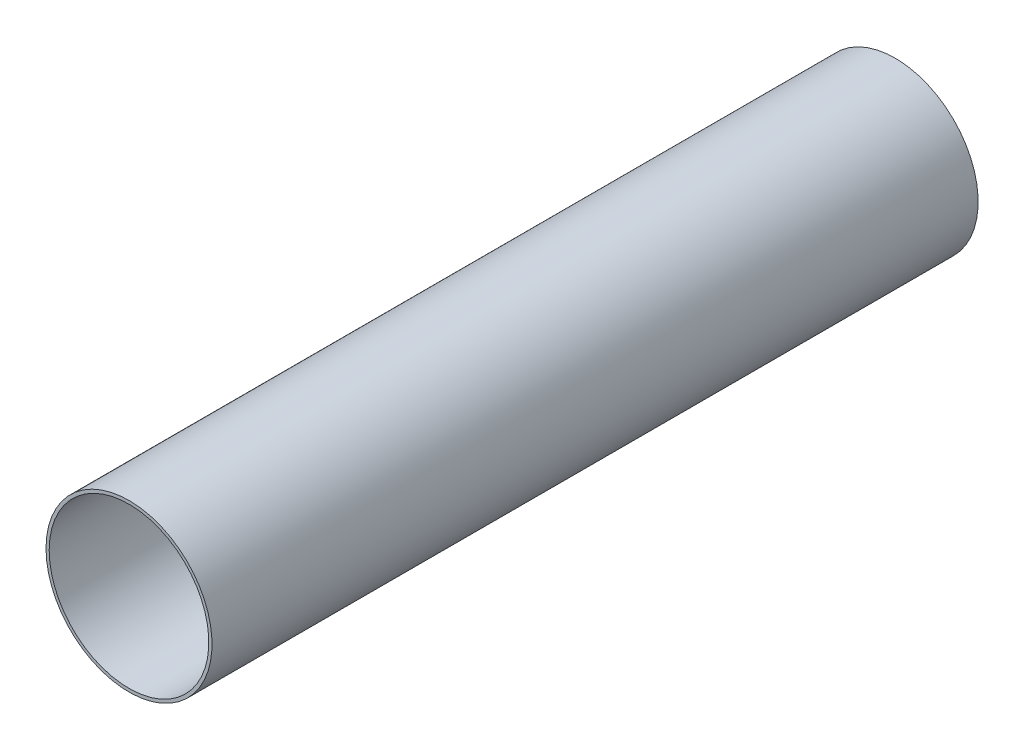
SolidWorks part; units mm, degrees
ref_plane "Front Plane" through (0, 0, 0) normal (0, 0, 1) x (1, 0, 0)
ref_plane "Top Plane" through (0, 0, 0) normal (0, 1, 0) x (1, 0, 0)
ref_plane "Right Plane" through (0, 0, 0) normal (1, 0, 0) x (0, 0, -1)
sketch "Sketch2" plane through (0, 0, 0) normal (0, 0, 1) x (1, 0, 0)
  circle A0 centre (0, 0) radius 12.5
  circle A1 centre (0, 0) radius 13
  dimension "D1" = 25
  dimension "D2" = 26
extrude "Boss-Extrude1" add sketch "Sketch2" along normal mid plane 120
